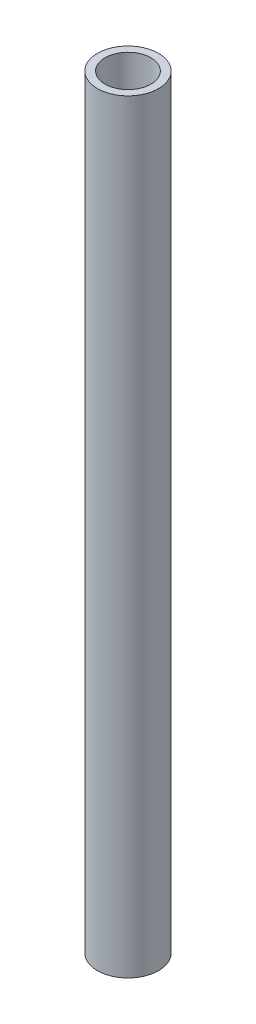
SolidWorks part; units mm, degrees
ref_plane "前视基准面" through (0, 0, 0) normal (0, 0, 1) x (1, 0, 0)
ref_plane "上视基准面" through (0, 0, 0) normal (0, 1, 0) x (1, 0, 0)
ref_plane "右视基准面" through (0, 0, 0) normal (1, 0, 0) x (0, 0, -1)
sketch "草图1" plane through (0, 0, 0) normal (0, 1, 0) x (1, 0, 0)
  circle A0 centre (0, 0) radius 4
  circle A1 centre (0, 0) radius 3
  dimension "D1" = 6
  dimension "D2" = 8
extrude "凸台-拉伸1" add sketch "草图1" along normal blind 100
